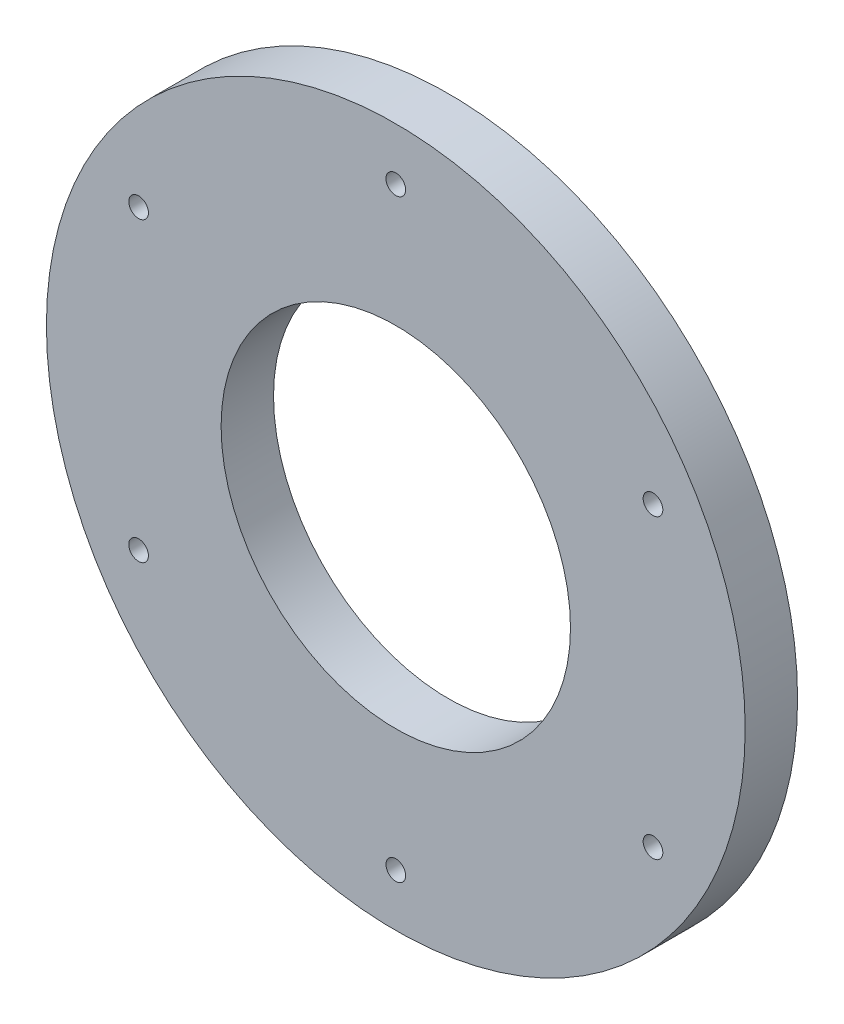
SolidWorks part; units mm, degrees
material "6061 Alloy"
ref_plane "Front Plane" through (0, 0, 0) normal (0, 0, 1) x (1, 0, 0)
ref_plane "Top Plane" through (0, 0, 0) normal (0, 1, 0) x (1, 0, 0)
ref_plane "Right Plane" through (0, 0, 0) normal (1, 0, 0) x (0, 0, -1)
sketch "Sketch1" plane through (0, 0, 0) normal (0, 0, 1) x (1, 0, 0)
  circle A0 centre (0, 0) radius 127
  dimension "D1" = 254
extrude "Boss-Extrude1" add sketch "Sketch1" along normal blind 19.05
sketch "Sketch2" plane through (0, 0, 19.05) normal (0, 0, 1) x (1, 0, 0)
  circle A0 centre (0, 0) radius 107.95
  point P1 (0, 107.95)
  point P6 (93.4874, 53.975)
  point P9 (93.4874, -53.975)
  point P10 (0, -107.95)
  point P11 (-93.4874, -53.975)
  point P12 (-93.4874, 53.975)
  dimension "D1" = 215.9
  dimension "D2" = 6
hole_wizard "1/4 Clearance Hole1" positions "Sketch2" profile "Sketch3" hole size "1/4" standard "ANSI Inch" end condition up to next
sketch "Sketch3" plane through (-93.4874, 53.975, 19.05) normal (1, 0, 0) x (0, -1, 0)
  line L0 (0, 0) -> (0, 19.05)
  line L1 (0, 19.05) -> (3.5712, 19.05)
  line L2 (3.5712, 19.05) -> (3.5712, 0)
  line L5 (3.5712, 0) -> (0, 0)
  line L11 (0, -6.35) -> (0, 107.95) construction
  dimension "Thru Hole Dia." = 7.1425
  dimension "Thru Hole Depth" = 19.05
sketch "Sketch4" plane through (0, 0, 19.05) normal (0, 0, 1) x (1, 0, 0)
  circle A0 centre (0, 0) radius 63.5
  dimension "D1" = 127
extrude "Cut-Extrude1" cut sketch "Sketch4" against normal up to next
